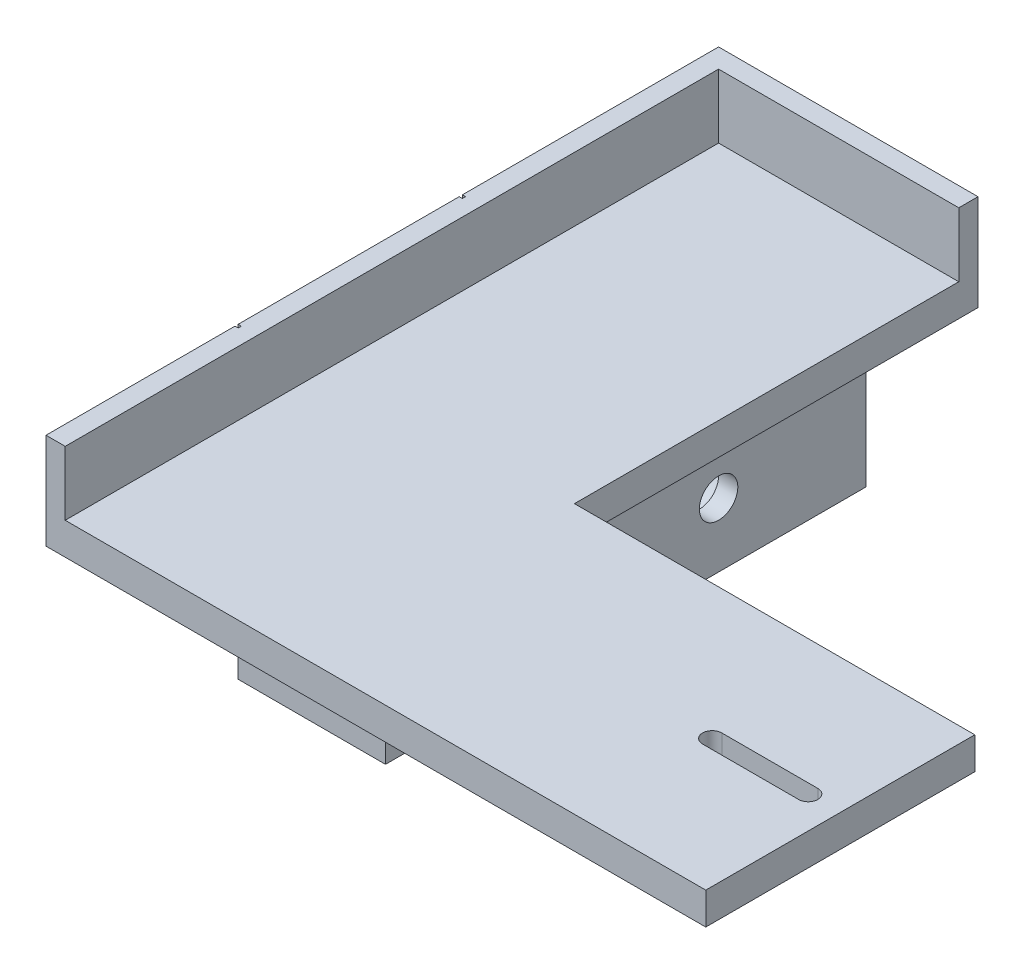
SolidWorks part; units mm, degrees
ref_plane "前视基准面" through (0, 0, 0) normal (0, 0, 1) x (1, 0, 0)
ref_plane "上视基准面" through (0, 0, 0) normal (0, 1, 0) x (1, 0, 0)
ref_plane "右视基准面" through (0, 0, 0) normal (1, 0, 0) x (0, 0, -1)
other "Configuration Table"
sketch "草图1" plane through (0, 0, 0) normal (0, 1, 0) x (1, 0, 0)
  line L0 (0, 0) -> (0, -37471.6343) construction
  line L1 (37.5, 23.0496) -> (37.5, -37448.5847) construction
  line L2 (-37.5, 33.9691) -> (-37.5, -37437.6651) construction
  line L3 (23.0851, 76) -> (-37448.5491, 76) construction
  line L4 (27.6828, -76) -> (-37443.9514, -76) construction
  line L5 (-37.5, 76) -> (-37.5, -26)
  line L6 (-37.5, -26) -> (37.5, -26)
  line L7 (37.5, -26) -> (37.5, 16)
  line L8 (37.5, 16) -> (0, 16)
  line L9 (0, 16) -> (0, 76)
  line L10 (0, 76) -> (-37.5, 76)
  dimension "D1" = 75
  dimension "D2" = 152
  dimension "D3" = 76
  dimension "D4" = 37.5
  dimension "D5" = 60
  dimension "D6" = 50
extrude "凸台-拉伸1" add sketch "草图1" along normal blind 5
sketch "草图2" plane through (0, 0, 0) normal (0, -1, 0) x (1, 0, 0)
  line L0 (0, -76) -> (-37.5, -76) construction
  line L1 (-37.5, -4) -> (-17.5, -4)
  line L2 (-37.5, -4) -> (-37.5, -76)
  line L3 (-37.5, -76) -> (-17.5, -76)
  line L4 (-17.5, -4) -> (-17.5, -76)
  line L5 (-37.5, 26) -> (37.5, 26) construction
  line L6 (-37.5, -76) -> (-37.5, 26) construction
  dimension "D1" = 20
  dimension "D2" = 30
extrude "凸台-拉伸2" add sketch "草图2" along normal blind 33
sketch "草图3" plane through (-37.5, 0, 0) normal (-1, 0, 0) x (0, 0, 1)
  line L0 (-72.3701, -23) -> (49927.6299, -23) construction
  line L1 (-4, -33) -> (-76, -33) construction
  line L2 (-76, 5) -> (-76, -33) construction
  line L3 (-4, -33) -> (-4, 0) construction
  circle A0 centre (-56, -23) radius 3
  circle A1 centre (-24, -23) radius 3
  dimension "D2" = 6
  dimension "D3" = 6
  dimension "D1" = 10
  dimension "D4" = 20
  dimension "D5" = 20
extrude "切除-拉伸1" cut sketch "草图3" against normal blind 30
sketch "草图4" plane through (-37.5, 0, 0) normal (-1, 0, 0) x (0, 0, 1)
  circle A0 centre (-56, -23) radius 5
  circle A1 centre (-24, -23) radius 5
  dimension "D1" = 10
  dimension "D2" = 10
extrude "切除-拉伸2" cut sketch "草图4" against normal blind 17
sketch "草图5" plane through (-37.5, 0, 0) normal (-1, 0, 0) x (0, 0, 1)
  line L0 (-76, 5) -> (26, 5)
  line L1 (26, 5) -> (26, 0)
  line L2 (26, 5) -> (26, 0) construction
  line L3 (26, 0) -> (-4, 0)
  line L4 (-4, 0) -> (-4, -33)
  line L5 (-4, -33) -> (-76, -33)
  line L6 (-76, -33) -> (-76, 5)
  circle A0 centre (-56, -23) radius 5
  circle A1 centre (-24, -23) radius 5
extrude "凸台-拉伸3" add sketch "草图5" along normal blind 3
sketch "草图6" plane through (0, 0, -76) normal (0, 0, -1) x (-1, 0, 0)
  line L0 (0, 5) -> (0, 0)
  line L1 (0, 0) -> (17.5, 0)
  line L2 (17.5, 0) -> (17.5, -33)
  line L3 (40.5, -33) -> (17.5, -33) construction
  line L4 (17.5, -33) -> (17.5, 0) construction
  line L5 (17.5, -33) -> (40.5, -33)
  line L6 (40.5, -33) -> (40.5, 5)
  line L7 (40.5, 5) -> (40.5, -33) construction
  line L8 (0, 5) -> (40.5, 5) construction
  line L9 (40.5, 5) -> (0, 5)
extrude "凸台-拉伸4" add sketch "草图6" along normal blind 3
sketch "草图7" plane through (0, 5, 0) normal (0, 1, 0) x (1, 0, 0)
  line L0 (0, 76) -> (0, 79)
  line L1 (0, 16) -> (0, 79) construction
  line L2 (0, 79) -> (-40.5, 79)
  line L3 (-40.5, 79) -> (-40.5, -26)
  line L4 (-40.5, -26) -> (-37.5, -26)
  line L5 (-40.5, -26) -> (37.5, -26) construction
  line L6 (-37.5, -26) -> (-37.5, 76)
  line L7 (-37.5, 76) -> (0, 76)
  dimension "D1" = 3
  dimension "D2" = 3
extrude "凸台-拉伸5" add sketch "草图7" along normal blind 10
sketch "草图8" plane through (37.5, 0, 0) normal (1, 0, 0) x (0, 0, -1)
  line L1 (-26, 5) -> (16, 5)
  line L2 (-26, 5) -> (-26, 0)
  line L3 (-26, 0) -> (16, 0)
  line L4 (16, 5) -> (16, 0)
extrude "凸台-拉伸6" add sketch "草图8" along normal blind 25
sketch "草图9" plane through (0, 5, 0) normal (0, 1, 0) x (1, 0, 0)
  line L0 (62.5, -5) -> (-40.5, -5) construction
  line L1 (62.5, 16) -> (62.5, -26) construction
  line L2 (-40.5, 79) -> (-40.5, -26) construction
  line L3 (55.875, -3.5) -> (-49944.125, -3.5) construction
  line L4 (51.668, -6.5) -> (-49948.332, -6.5) construction
  line L5 (37.5, 10.0614) -> (37.5, -49989.9386) construction
  line L6 (42.5, 8.5033) -> (42.5, -49991.4967) construction
  line L7 (57.5, 0.9587) -> (57.5, -49999.0413) construction
  line L8 (57.5, -3.5) -> (42.5, -3.5)
  line L9 (42.5, -6.5) -> (57.5, -6.5)
  arc A0 (42.5, -6.5) -> (42.5, -3.5) centre (42.5, -5) cw
  arc A1 (57.5, -3.5) -> (57.5, -6.5) centre (57.5, -5) cw
  dimension "D1" = 1.5
  dimension "D2" = 1.5
  dimension "D3" = 25
  dimension "D4" = 5
  dimension "D5" = 5
extrude "切除-拉伸3" cut sketch "草图9" against normal blind 10
sketch "草图10" plane through (-40.5, 0, 0) normal (-1, 0, 0) x (0, 0, 1)
  line L0 (-79, -33) -> (-79, 15) construction
  line L1 (-4, 0) -> (-79, 0)
  line L2 (-4, 0) -> (-4, -0.5)
  line L3 (-4, -0.5) -> (-79, -0.5)
  line L4 (-79, 0) -> (-79, -0.5)
  dimension "D1" = 0.5
extrude "切除-拉伸4" cut sketch "草图10" against normal blind 0.5
sketch "草图11" plane through (-40.5, 0, 0) normal (-1, 0, 0) x (0, 0, 1)
  line L0 (-79, 0) -> (26, 0) construction
  line L1 (-4, 0) -> (-3.5, 0)
  line L2 (-4, 0) -> (-4, 15)
  line L3 (-4, 15) -> (-3.5, 15)
  line L4 (-3.5, 0) -> (-3.5, 15)
  line L5 (-4, 0) -> (-79, 0) construction
  line L6 (-79, 15) -> (26, 15) construction
  line L7 (-79, -33) -> (-4, -33) construction
  line L8 (-39, 15) -> (-38.5, 15)
  line L9 (-39, 15) -> (-39, -33)
  line L10 (-39, -33) -> (-38.5, -33)
  line L11 (-38.5, 15) -> (-38.5, -33)
  line L12 (-4, -33) -> (-4, -0.5) construction
  line L13 (-79, 0) -> (-79, 15) construction
  dimension "D1" = 0.5
  dimension "D2" = 0.5
  dimension "D3" = 40
extrude "切除-拉伸5" cut sketch "草图11" against normal blind 0.5
